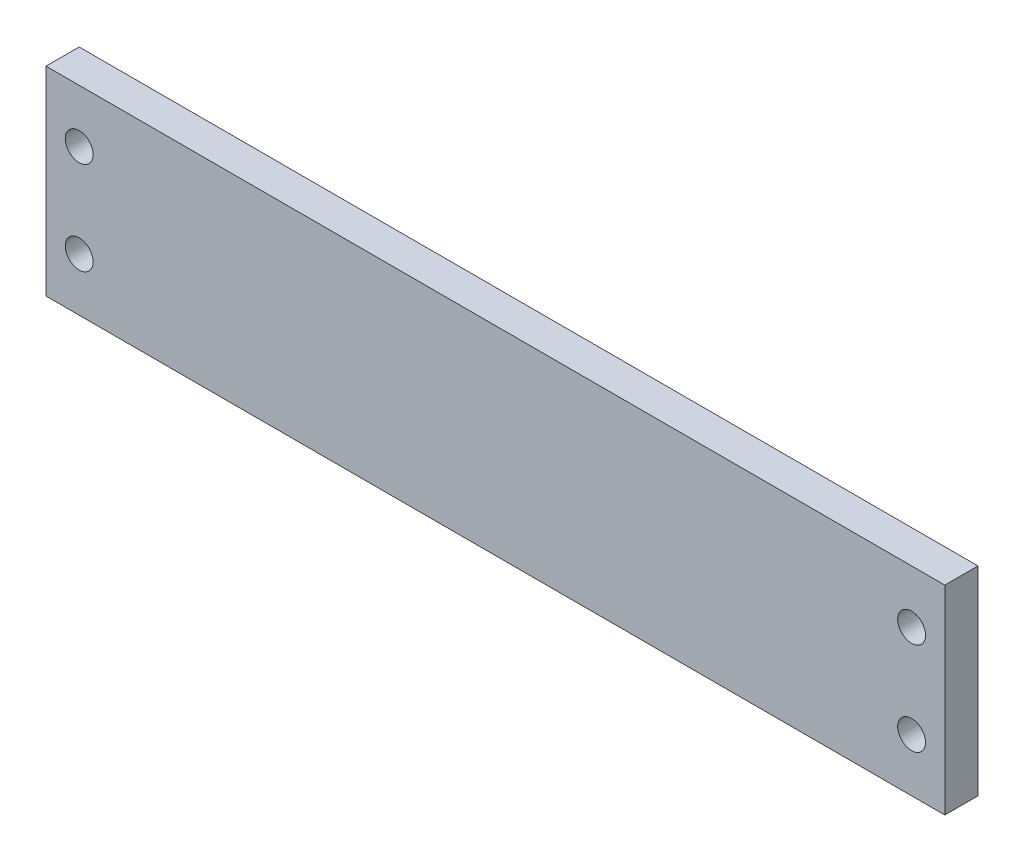
SolidWorks part; units mm, degrees
ref_plane "Plan de face" through (0, 0, 0) normal (0, 0, 1) x (1, 0, 0)
ref_plane "Plan de dessus" through (0, 0, 0) normal (0, 1, 0) x (1, 0, 0)
ref_plane "Plan de droite" through (0, 0, 0) normal (1, 0, 0) x (0, 0, -1)
sketch "Esquisse1" plane through (0, 0, 0) normal (0, 0, 1) x (1, 0, 0)
  line L1 (0, 0) -> (-135.42, 0)
  line L2 (0, 0) -> (0, 30)
  line L3 (0, 30) -> (-135.42, 30)
  line L4 (-135.42, 0) -> (-135.42, 30)
  circle A0 centre (-5, 22) radius 2.1
  circle A1 centre (-130.42, 8) radius 2.1
  circle A2 centre (-5, 8) radius 2.1
  circle A3 centre (-130.42, 22) radius 2.1
  dimension "D4" = 4.2
  dimension "D6" = 4.2
  dimension "D11" = 4.2
  dimension "D13" = 4.2
  dimension "D1" = 135.42
  dimension "D2" = 30
  dimension "D3" = 5
  dimension "D5" = 8
  dimension "D7" = 5
  dimension "D8" = 8
  dimension "D9" = 8
  dimension "D10" = 5
  dimension "D12" = 5
  dimension "D14" = 8
extrude "Boss.-Extru.1" add sketch "Esquisse1" along normal blind 5
